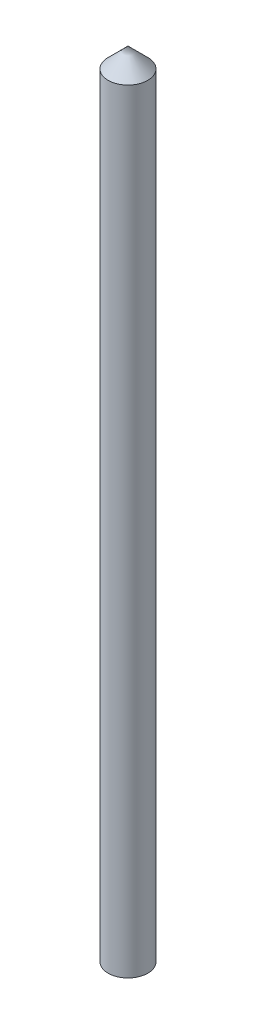
SolidWorks part; units mm, degrees
ref_plane "Front Plane" through (0, 0, 0) normal (0, 0, 1) x (1, 0, 0)
ref_plane "Top Plane" through (0, 0, 0) normal (0, 1, 0) x (1, 0, 0)
ref_plane "Right Plane" through (0, 0, 0) normal (1, 0, 0) x (0, 0, -1)
sketch "Sketch1" plane through (0, 0, 0) normal (0, 1, 0) x (1, 0, 0)
  circle A0 centre (0, 0) radius 3
  dimension "D1" = 6
extrude "Boss-Extrude1" add sketch "Sketch1" along normal blind 120
chamfer "Chamfer1" distance 3 angle 45 1 edges at (0, 120, 3)
